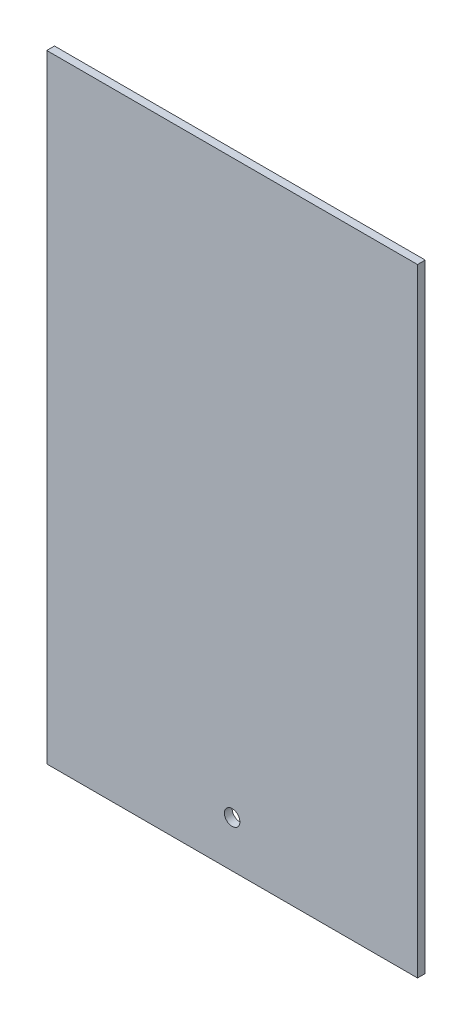
SolidWorks part; units mm, degrees
ref_plane "Front Plane" through (0, 0, 0) normal (0, 0, 1) x (1, 0, 0)
ref_plane "Top Plane" through (0, 0, 0) normal (0, 1, 0) x (1, 0, 0)
ref_plane "Right Plane" through (0, 0, 0) normal (1, 0, 0) x (0, 0, -1)
sketch "Sketch1" plane through (0, 0, 0) normal (0, 0, 1) x (1, 0, 0)
  line L1 (-76.2, -127) -> (76.2, -127)
  line L2 (-76.2, -127) -> (-76.2, 127)
  line L3 (-76.2, 127) -> (76.2, 127)
  line L4 (76.2, -127) -> (76.2, 127)
  line L5 (-76.2, -127) -> (76.2, 127) construction
  line L6 (-76.2, 127) -> (76.2, -127) construction
  point P0 (0, 0)
  dimension "D1" = 152.4
  dimension "D2" = 254
extrude "Boss-Extrude1" add sketch "Sketch1" along normal blind 3.175
sketch "Sketch2" plane through (0, 0, 3.175) normal (0, 0, 1) x (1, 0, 0)
  line L0 (-76.2, -127) -> (76.2, -127) construction
  circle A0 centre (0, -107.95) radius 3.175
  dimension "D1" = 6.35
  dimension "D2" = 19.05
extrude "Cut-Extrude1" cut sketch "Sketch2" against normal through all
